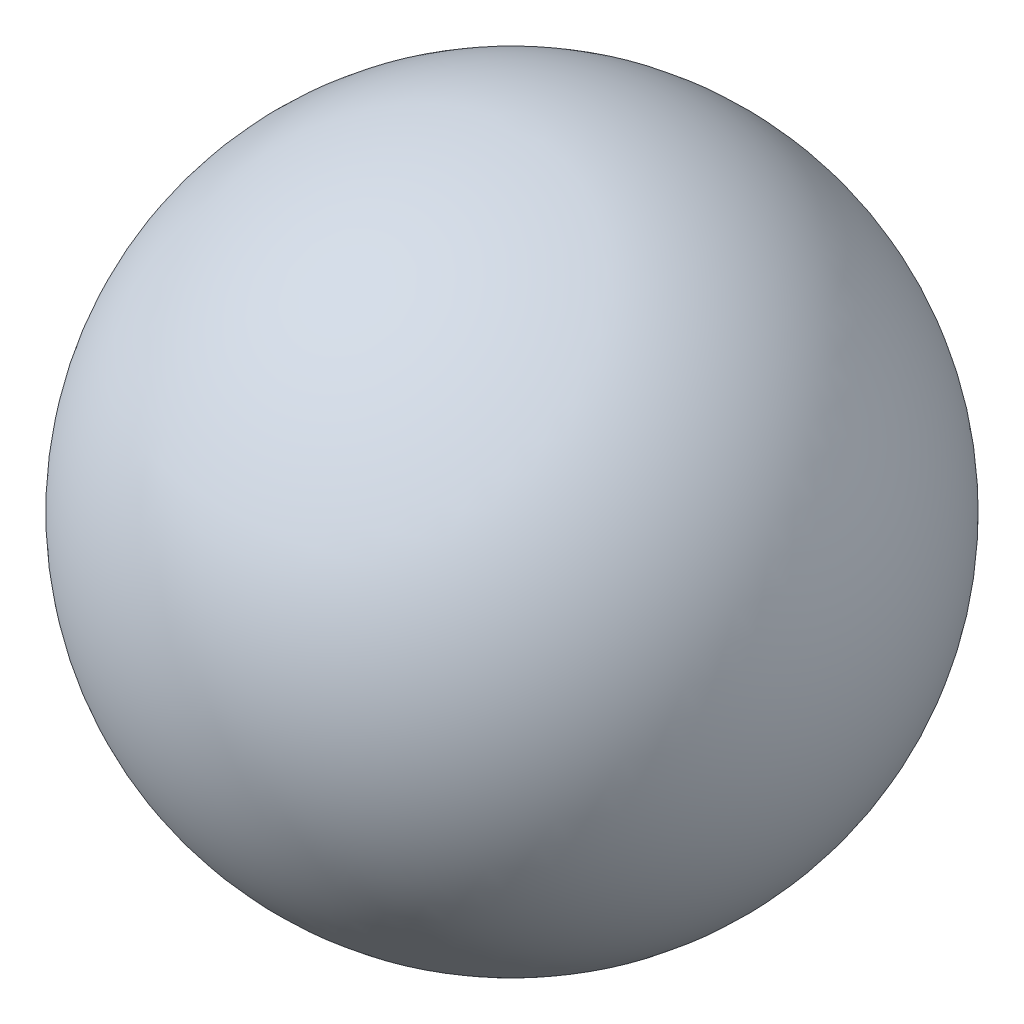
SolidWorks part; units mm, degrees
material "Alloy Steel (SS)"
ref_plane "Front Plane" through (0, 0, 0) normal (0, 0, 1) x (1, 0, 0)
ref_plane "Top Plane" through (0, 0, 0) normal (0, 1, 0) x (1, 0, 0)
ref_plane "Right Plane" through (0, 0, 0) normal (1, 0, 0) x (0, 0, -1)
sketch "Sketch1" plane through (0, 0, 0) normal (0, 0, 1) x (1, 0, 0)
  line L0 (0, -15.875) -> (0, 15.875) construction
  line L1 (0, -15.875) -> (0, 15.875)
  arc A0 (0, -15.875) -> (0, 15.875) centre (0, 0) ccw
  point P3 (0, 0)
  dimension "D1" = 31.75
revolve "Revolve1" add sketch "Sketch1" angle 360 about L0
